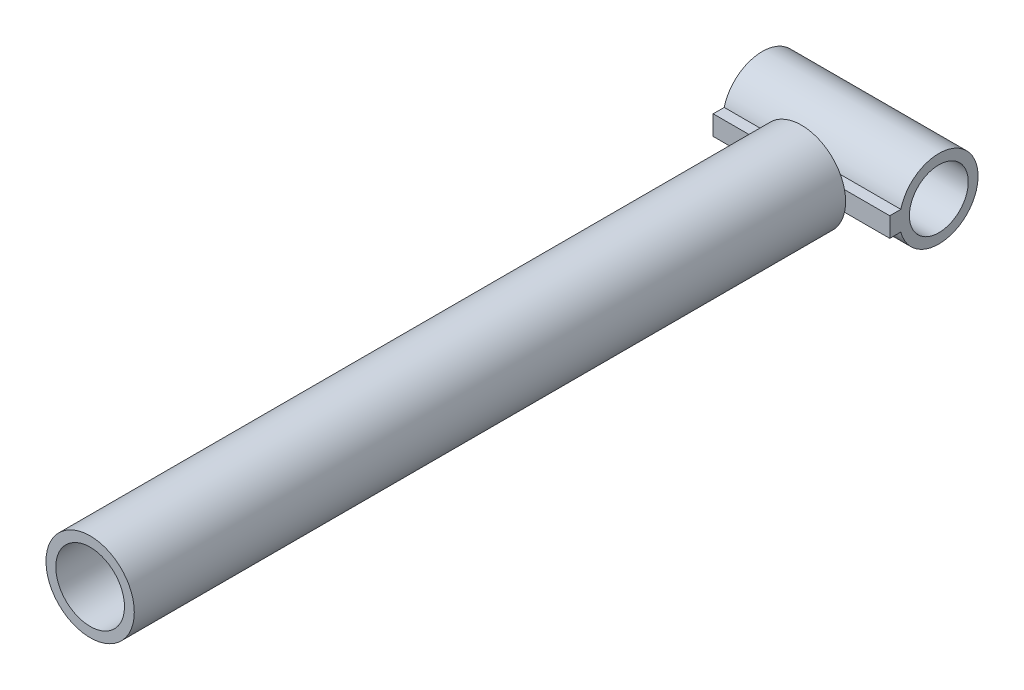
SolidWorks part; units mm, degrees
material "AISI 1020"
ref_plane "Ön Düzlem" through (0, 0, 0) normal (0, 0, 1) x (1, 0, 0)
ref_plane "Üst Düzlem" through (0, 0, 0) normal (0, 1, 0) x (1, 0, 0)
ref_plane "Sağ Düzlem" through (0, 0, 0) normal (1, 0, 0) x (0, 0, -1)
sketch "Çizim1" plane through (0, 0, 0) normal (0, 0, 1) x (1, 0, 0)
  circle A0 centre (0, 0) radius 45
  dimension "D1" = 90
extrude "Yükseklik-Ekstrüzyon1" add sketch "Çizim1" along normal blind 725
sketch "Çizim2" plane through (0, 0, 725) normal (0, 0, 1) x (1, 0, 0)
  circle A0 centre (0, 0) radius 35
  dimension "D1" = 70
extrude "Kes-Ekstrüzyon1" cut sketch "Çizim2" against normal blind 600
sketch "Çizim3" plane through (0, 0, 0) normal (1, 0, 0) x (0, 0, -1)
  line L0 (0, 0) -> (50, 0) construction
  line L1 (0, -45) -> (0, 45) construction
  line L2 (0, 10) -> (11.2702, 10)
  line L3 (0, -10) -> (11.2702, -10)
  line L4 (0, 10) -> (50, 10) construction
  line L5 (0, -10) -> (50, -10) construction
  line L6 (0, 10) -> (0, -10)
  circle A0 centre (50, 0) radius 30
  arc A1 (11.2702, -10) -> (11.2702, 10) centre (50, 0) ccw
  dimension "D2" = 80
  dimension "D3" = 60
  dimension "D1" = 50
  dimension "D4" = 10
  dimension "D5" = 10
extrude "Yükseklik-Ekstrüzyon2" add sketch "Çizim3" along normal mid plane 180
